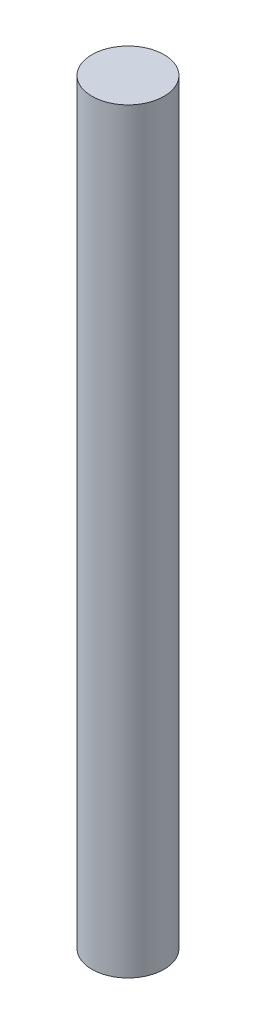
SolidWorks part; units mm, degrees
ref_plane "Спереди" through (0, 0, 0) normal (0, 0, 1) x (1, 0, 0)
ref_plane "Сверху" through (0, 0, 0) normal (0, 1, 0) x (1, 0, 0)
ref_plane "Справа" through (0, 0, 0) normal (1, 0, 0) x (0, 0, -1)
sketch "Эскиз1" plane through (0, 0, 0) normal (0, 1, 0) x (1, 0, 0)
  circle A0 centre (0, 0) radius 16.7
extrude "Бобышка-Вытянуть1" add sketch "Эскиз1" along normal blind 350
